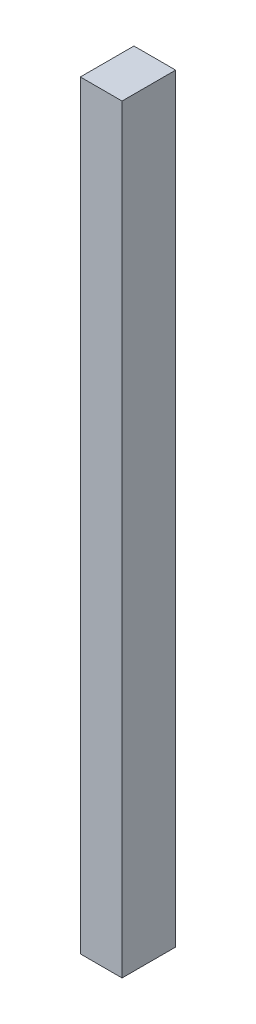
SolidWorks part; units mm, degrees
material "Plain Carbon Steel"
ref_plane "Front Plane" through (0, 0, 0) normal (0, 0, 1) x (1, 0, 0)
ref_plane "Top Plane" through (0, 0, 0) normal (0, 1, 0) x (1, 0, 0)
ref_plane "Right Plane" through (0, 0, 0) normal (1, 0, 0) x (0, 0, -1)
sketch "Sketch1" plane through (0, 0, 0) normal (0, 1, 0) x (1, 0, 0)
  line L0 (0, 0) -> (38.45, 0)
  line L1 (38.45, 0) -> (38.45, -49.4)
  line L2 (38.45, -49.4) -> (0, -49.4)
  line L3 (0, -49.4) -> (0, 0)
  dimension "D1" = 49.4
  dimension "D2" = 38.45
extrude "Boss-Extrude1" add sketch "Sketch1" along normal blind 700
